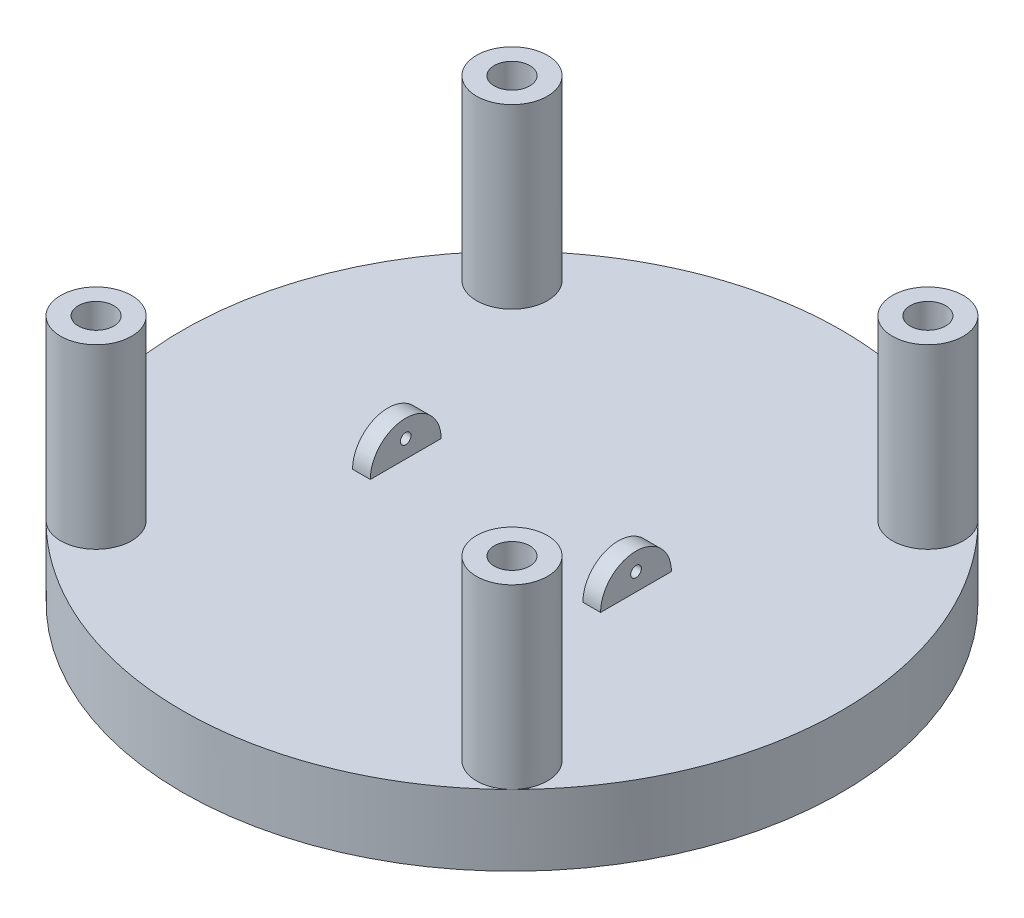
SolidWorks part; units mm, degrees
ref_plane "Front Plane" through (0, 0, 0) normal (0, 0, 1) x (1, 0, 0)
ref_plane "Top Plane" through (0, 0, 0) normal (0, 1, 0) x (1, 0, 0)
ref_plane "Right Plane" through (0, 0, 0) normal (1, 0, 0) x (0, 0, -1)
sketch "Sketch1" plane through (0, 0, 0) normal (0, 1, 0) x (1, 0, 0)
  circle A0 centre (0, 0) radius 93
  dimension "D1" = 186
extrude "Boss-Extrude1" add sketch "Sketch1" along normal blind 20
shell "Shell1" thickness 3
sketch "Sketch2" plane through (0, 20, 0) normal (0, 1, 0) x (1, 0, 0)
  line L0 (0, 0) -> (-93, 0) construction
  line L1 (-35, 10) -> (-30, 10)
  line L2 (-35, 10) -> (-35, 0)
  line L4 (-30, 10) -> (-30, 0)
  line L5 (-35, 0) -> (-30, 0)
  circle A0 centre (0, 0) radius 93 construction
  dimension "D1" = 5
  dimension "D2" = 10
  dimension "D3" = 30
revolve "Revolve1" add sketch "Sketch2" angle 180 about L0
sketch "Sketch7" plane through (-35, 0, 0) normal (-1, 0, 0) x (0, 0, 1)
  line L0 (0, 20) -> (0, 30) construction
  line L1 (10, 20) -> (-10, 20) construction
  circle A0 centre (0, 25) radius 1.5
  arc A1 (10, 20) -> (-10, 20) centre (0, 20) ccw construction
  point P9 (0, 0)
  dimension "D1" = 3
extrude "Cut-Extrude1" cut sketch "Sketch7" against normal blind 10
mirror "Mirror1" about plane through (0, 0, 0) normal (1, 0, 0) of "Revolve1", "Cut-Extrude1"
sketch "Sketch8" plane through (0, 17, 0) normal (0, -1, 0) x (1, 0, 0)
  line L0 (0, 0) -> (0, 90) construction
  line L1 (-20, 40) -> (20, 40)
  line L2 (-20, 40) -> (-20, 80)
  line L3 (-20, 80) -> (20, 80)
  line L4 (20, 40) -> (20, 80)
  line L5 (-20, 40) -> (20, 80) construction
  line L6 (-20, 80) -> (20, 40) construction
  circle A0 centre (0, 0) radius 90 construction
  point P0 (0, 60)
  point P11 (0, 0)
  dimension "D1" = 40
  dimension "D2" = 40
  dimension "D3" = 40
extrude "Cut-Extrude2" cut sketch "Sketch8" against normal blind 2
mirror "Mirror2" about plane through (0, 0, 0) normal (0, 0, 1) of "Cut-Extrude2"
sketch "Sketch9" plane through (0, 20, 0) normal (0, 1, 0) x (1, 0, 0)
  line L0 (0, 0) -> (-65.7609, 65.7609) construction
  line L1 (0, 0) -> (65.7609, -65.7609) construction
  line L2 (-65.7609, -65.7609) -> (65.7609, 65.7609) construction
  line L3 (-93, 0) -> (93, 0) construction
  circle A0 centre (0, 0) radius 93 construction
  circle A1 centre (-58.6899, 58.6899) radius 10
  point P9 (0, 0)
  point P12 (0, 0)
  point P16 (0, 0)
  dimension "D3" = 20
  dimension "D1" = 90
  dimension "D2" = 45
extrude "Boss-Extrude2" add sketch "Sketch9" along normal blind 50
sketch "Sketch10" plane through (0, 70, 0) normal (0, 1, 0) x (1, 0, 0)
  circle A0 centre (-58.6899, 58.6899) radius 5
  dimension "D1" = 10
extrude "Cut-Extrude3" cut sketch "Sketch10" against normal blind 20
pattern_circular "CirPattern1" count 4 over 360 about axis through (0, 0, 0) along (0, 1, 0) of "Cut-Extrude3", "Boss-Extrude2"
